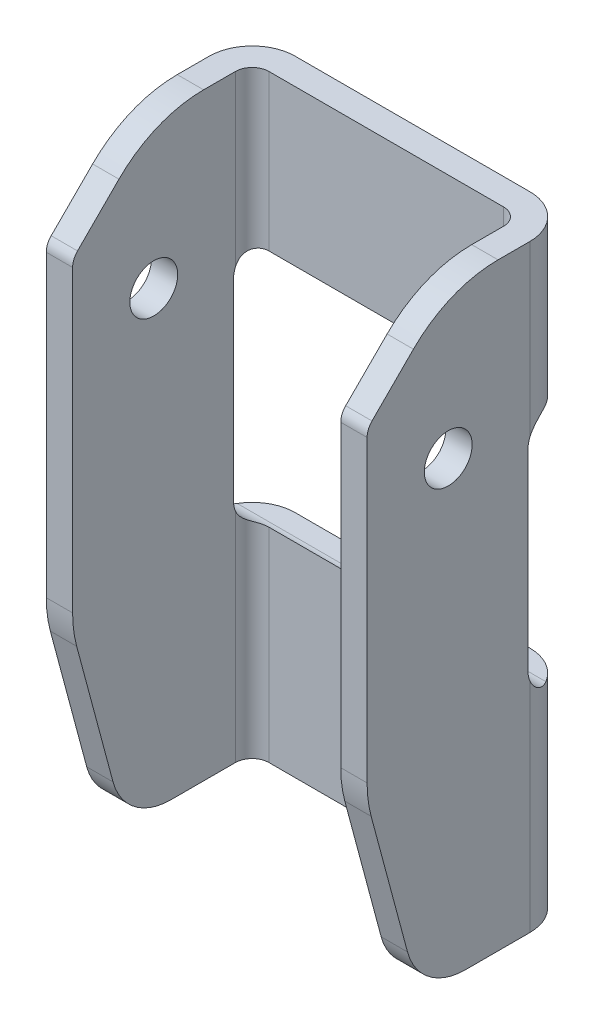
SolidWorks part; units mm, degrees
ref_plane "Front Plane" through (0, 0, 0) normal (0, 0, 1) x (1, 0, 0)
ref_plane "Top Plane" through (0, 0, 0) normal (0, 1, 0) x (1, 0, 0)
ref_plane "Right Plane" through (0, 0, 0) normal (1, 0, 0) x (0, 0, -1)
sketch "Sketch1" plane through (0, 0, 0) normal (0, 0, 1) x (1, 0, 0)
  line L1 (-17.018, 31.75) -> (17.018, 31.75)
  line L2 (-17.018, 31.75) -> (-17.018, -31.75)
  line L3 (-17.018, -31.75) -> (17.018, -31.75)
  line L4 (17.018, 31.75) -> (17.018, -31.75)
  line L5 (-17.018, 31.75) -> (17.018, -31.75) construction
  line L6 (-17.018, -31.75) -> (17.018, 31.75) construction
  point P0 (0, 0)
  dimension "D1" = 34.036
  dimension "D2" = 63.5
extrude "Boss-Extrude1" add sketch "Sketch1" along normal blind 21.844
sketch "Sketch2" plane through (0, 0, 0) normal (0, 1, 0) x (1, 0, 0)
  line L9 (14.224, -21.844) -> (14.224, -2.794)
  line L10 (14.224, -2.794) -> (-14.224, -2.794)
  line L11 (-14.224, -2.794) -> (-14.224, -21.844)
  line L12 (14.224, -21.844) -> (14.224, -2.794)
  line L13 (14.224, -2.794) -> (-14.224, -2.794)
  line L14 (-14.224, -2.794) -> (-14.224, -21.844)
  dimension "D1" = 2.794
extrude "Cut-Extrude1" cut sketch "Sketch2" against normal through all both and the other way through all
sketch "Sketch3" plane through (0, 0, 0) normal (1, 0, 0) x (0, 0, -1)
  line L1 (-2.2352, 15.3162) -> (2.9572, 15.3162)
  line L2 (-4.7752, -31.75) -> (-4.7752, 31.75)
  line L3 (-4.7752, -7.6454) -> (-4.7752, 12.7762)
  line L4 (-2.2352, -10.1854) -> (2.9572, -10.1854)
  line L5 (-21.844, 31.75) -> (0, 31.75) construction
  line L6 (-21.844, -31.75) -> (0, -31.75) construction
  line L7 (2.9572, 15.3162) -> (2.9572, -10.1854)
  line L8 (-13.208, 31.75) -> (-21.844, 23.114)
  line L9 (-13.208, 31.75) -> (-13.208, 40.5314)
  line L10 (-13.208, 40.5314) -> (-30.1925, 40.5314)
  line L11 (-30.1925, 40.5314) -> (-30.1925, 23.114)
  line L12 (-21.844, 23.114) -> (-30.1925, 23.114)
  line L13 (-21.844, -31.75) -> (-21.844, 31.75) construction
  line L14 (-16.256, -31.8895) -> (-16.256, -43.2893)
  line L15 (-16.256, -31.8895) -> (-25.9709, 4.3669)
  line L16 (-25.9709, 4.3669) -> (-30.9865, 4.3669)
  line L17 (-30.9865, 4.3669) -> (-30.9865, -43.2893)
  line L18 (-30.9865, -43.2893) -> (-16.256, -43.2893)
  arc A0 (-2.2352, -10.1854) -> (-4.7752, -7.6454) centre (-2.2352, -7.6454) cw
  arc A1 (-4.7752, 12.7762) -> (-2.2352, 15.3162) centre (-2.2352, 12.7762) cw
  circle A2 centre (-13.2334, 16.1544) radius 2.54
  point P24 (-13.208, 36.1407)
  dimension "D4" = 2.54
  dimension "D12" = 5.08
  dimension "D2" = 16.4338
  dimension "D3" = 21.5646
  dimension "D5" = 8.636
  dimension "D6" = 8.636
  dimension "D7" = 45
  dimension "D8" = 5.588
  dimension "D9" = 15
  dimension "D10" = 8.6106
  dimension "D11" = 15.5956
  dimension "D1" = 4.7752
extrude "Cut-Extrude2" cut sketch "Sketch3" against normal through all both and the other way through all
fillet "Fillet1" radius 12.7
fillet "Fillet2" radius 6.35
fillet "Fillet3" radius 1.778
fillet "Fillet4" radius 4.572
